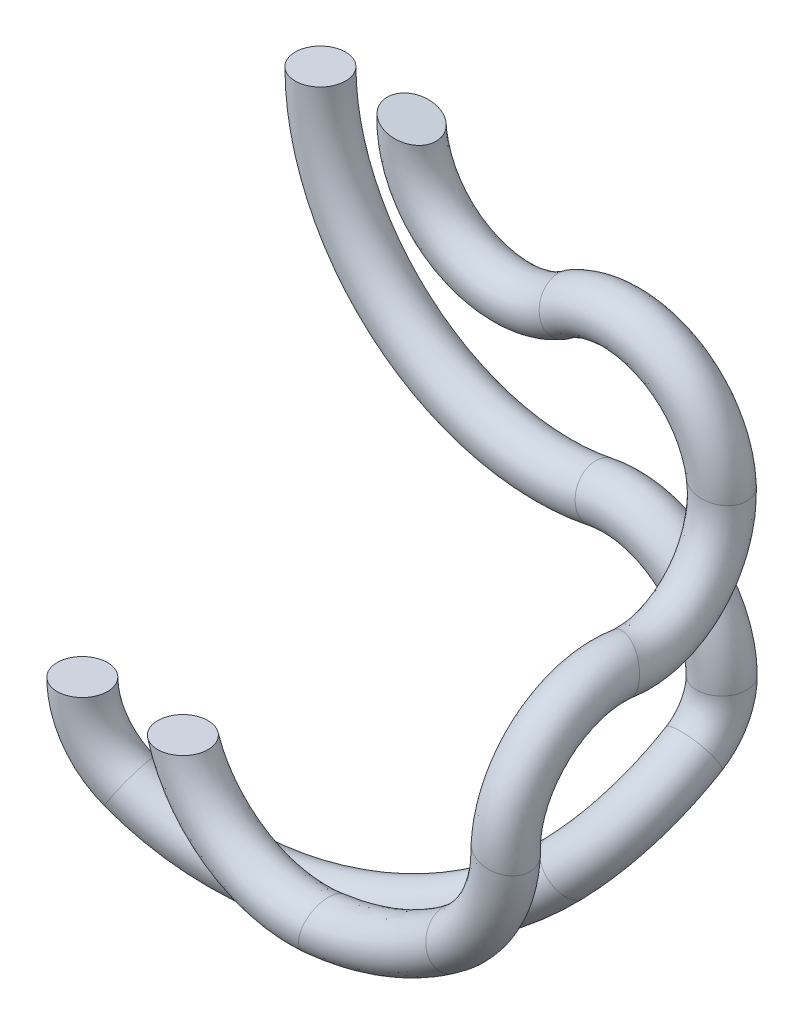
SolidWorks part; units mm, degrees
material "Magnesium Alloy"
ref_plane "Front Plane" through (0, 0, 0) normal (0, 0, 1) x (1, 0, 0)
ref_plane "Top Plane" through (0, 0, 0) normal (0, 1, 0) x (1, 0, 0)
ref_plane "Right Plane" through (0, 0, 0) normal (1, 0, 0) x (0, 0, -1)
sketch "Sketch2" plane through (0, 0, 0) normal (0, 1, 0) x (1, 0, 0)
  circle A0 centre (0, 0) radius 3
  dimension "D1" = 6
ref_plane "Plane1" through (37, 0, 0) normal (1, 0, 0) x (0, 0, -1)
ref_plane "Plane2" through (0, 0, -27.3) normal (0, 0, 1) x (1, 0, 0)
sketch "Sketch3" plane through (0, 0, 0) normal (0, 0, 1) x (1, 0, 0)
  line L0 (37, -15.125) -> (37, 15.125) construction
  arc A0 (0, 50) -> (18.4268, 40.0396) centre (11.9054, 50) ccw
  arc A1 (18.4268, 40.0396) -> (37, 30) centre (25, 30) cw
  dimension "D1" = 12
  dimension "D2" = 50
  dimension "D3" = 30
sketch "Sketch4" plane through (0, 0, 0) normal (1, 0, 0) x (0, 0, -1)
  line L0 (24.5, 30) -> (0, 30) construction
  line L1 (10.7134, 14.4646) -> (0, 0) construction
  arc A0 (10.7134, 14.4646) -> (16.4282, 18.6612) centre (20.3564, 7.3223) cw
  arc A1 (16.4282, 18.6612) -> (24.5, 30) centre (12.5, 30) ccw
  dimension "D2" = 12
  dimension "D4" = 12
  dimension "D1" = 24.5
  dimension "D3" = 18
sketch "Sketch6" plane through (0, 0, -27.3) normal (0, 0, 1) x (1, 0, 0)
  arc A0 (0, 50) -> (18.4268, 40.0396) centre (11.9054, 50) ccw construction
  arc A1 (37, 30) -> (18.4268, 40.0396) centre (25, 30) ccw construction
  arc A2 (0, 50) -> (18.4268, 40.0396) centre (11.9054, 50) ccw
  arc A3 (37, 30) -> (18.4268, 40.0396) centre (25, 30) ccw
sketch "Sketch7" plane through (37, 0, 0) normal (1, 0, 0) x (0, 0, -1)
  arc A0 (16.4282, 18.6612) -> (10.7134, 14.4646) centre (20.3564, 7.3223) ccw construction
  arc A1 (16.4282, 18.6612) -> (24.5, 30) centre (12.5, 30) ccw construction
  arc A2 (16.4282, 18.6612) -> (10.7134, 14.4646) centre (20.3564, 7.3223) ccw
  arc A3 (16.4282, 18.6612) -> (24.5, 30) centre (12.5, 30) ccw
sketch "Sketch8" plane through (0, 0, 0) normal (0, 0, 1) x (1, 0, 0)
  line L0 (3, 0) -> (-3, 0) construction
  arc A1 (0, 0) -> (16.848, -11) centre (15.0295, 4.6172) ccw
  arc A2 (16.848, -11) -> (32.1489, -4.9619) centre (13.1469, 20.7846) ccw
  arc A3 (32.1489, -4.9619) -> (37, 14.4646) centre (22.8124, 7.6885) ccw
  dimension "D1" = 31.9994
  dimension "D2" = 11
sketch3d "3DSketch2"
  line L0 (36.9546, 31.0431, -27.3) -> (38.5338, 7.49, 0) construction
  arc A1 (0, 0, 0) -> (16.848, -11, 0) centre (15.0295, 4.6172, 0) ccw construction
  arc A2 (16.848, -11, 0) -> (32.1489, -4.9619, 0) centre (13.1469, 20.7846, 0) ccw construction
  arc A3 (37, 30, -27.3) -> (18.4268, 40.0396, -27.3) centre (25, 30, -27.3) ccw construction
  arc A4 (0, 50, -27.3) -> (18.4268, 40.0396, -27.3) centre (11.9054, 50, -27.3) ccw construction
  arc A5 (32.1489, -4.9619, 0) -> (37, 14.4646, 0) centre (22.8124, 7.6885, 0) ccw construction
  arc A6 (38.4122, 19.5675, -13.9693) -> (38.5338, 7.49, 0) centre (38.2944, 7.493, -12.2015) ccw
  arc A7 (38.4122, 19.5675, -13.9693) -> (36.9546, 31.0431, -27.3) centre (37.351, 31.0777, -15.6292) ccw
  arc A8 (36.9546, 31.0431, -27.3) -> (18.4268, 40.0396, -27.3) centre (25, 30, -27.3) ccw
  arc A9 (0, 50, -27.3) -> (18.4268, 40.0396, -27.3) centre (11.9054, 50, -27.3) ccw
  arc A10 (0, 0, 0) -> (16.848, -11, 0) centre (15.0295, 4.6172, 0) ccw
  arc A11 (16.848, -11, 0) -> (32.1489, -4.9619, 0) centre (13.1469, 20.7846, 0) ccw
  arc A12 (32.1489, -4.9619, 0) -> (38.5338, 7.49, 0) centre (22.8124, 7.6885, 0) ccw
  point P3 (15.0295, 4.6172, 15.7227)
  point P13 (25, 30, -15.3)
  point P16 (11.9054, 50, -15.3946)
  point P17 (50.4949, 7.3389, -12.4409)
  point P18 (48.9776, 32.0921, -16.0272)
  point P19 (25, 30, -15.3)
  point P20 (11.9054, 50, -15.3946)
  point P23 (13.1469, 20.7846, 31.9994)
  point P24 (15.0295, 4.6172, 15.7227)
  point P26 (22.8124, 7.6885, 15.7227)
  point P27 (13.1469, 20.7846, 31.9994)
  point P28 (22.8124, 7.6885, 15.7227)
sweep "Sweep1" add profiles "Sketch2" path "3DSketch2"
sketch "Sketch9" plane through (0, 0, 0) normal (0, 0, 1) x (1, 0, 0)
  arc A0 (37, 0) -> (-12, 0) centre (12.5, 0) cw construction
  dimension "D1" = 12
sketch "Sketch10" plane through (37, 0, 0) normal (1, 0, 0) x (0, 0, -1)
  arc A0 (19.9191, 0.4646) -> (23.4888, 4.8271) centre (26.5822, -1.3458) cw
  arc A1 (23.4888, 4.8271) -> (27.3, 11) centre (20.3953, 11) ccw
  point P5 (0, 0)
  dimension "D1" = 14
  dimension "D2" = 11
sketch "Sketch11" plane through (0, 0, -27.3) normal (0, 0, 1) x (1, 0, 0)
  arc A0 (-10.89, 50) -> (22.5699, 22.7514) centre (16.9351, 50) ccw
  arc A1 (22.5699, 22.7514) -> (37, 11) centre (25, 11) cw
  dimension "D2" = 12
  dimension "D1" = 10.89
sketch3d "3DSketch3"
  line L0 (-12, 0, 0) -> (-12, 11.5276, 0) construction
  line L1 (-12, 0, 0) -> (31.5832, 0, 0) construction
  line L2 (31.5832, 0, 0) -> (31.5832, 0, -14) construction
  line L3 (31.5832, 0, -14) -> (31.5832, -4.9493, -14) construction
  line L4 (12, 0, 0) -> (12, 0, -6) construction
  line L5 (12, 0, -6) -> (12, -14, -6) construction
  arc A0 (-7.2107, -8.8412, -0.9153) -> (31.5832, -4.9493, -14) centre (8.3648, 18.4815, -11.2394) cw
  arc A2 (37, 4.8271, -23.4888) -> (37, 11, -27.3) centre (37, 11, -20.3953) ccw construction
  arc A3 (22.5699, 22.7514, -27.3) -> (37, 11, -27.3) centre (25, 11, -27.3) ccw construction
  arc A4 (-10.89, 50, -27.3) -> (22.5699, 22.7514, -27.3) centre (16.9351, 50, -27.3) ccw construction
  arc A6 (37, 5.1024, -23.9859) -> (37, 11, -27.3) centre (37, 11, -20.3953) ccw
  arc A7 (22.5699, 22.7514, -27.3) -> (37, 11, -27.3) centre (25, 11, -27.3) ccw
  arc A8 (-10.89, 50, -27.3) -> (22.5699, 22.7514, -27.3) centre (16.9351, 50, -27.3) ccw
  arc A9 (-12, 0, 0) -> (-7.2107, -8.8412, -0.9153) centre (-1.7323, 0, -1.9623) cw
  arc A10 (31.5832, -4.9493, -14) -> (37, 5.1024, -23.9859) centre (21.7451, -3.0586, -28.9545) cw
  arc A12 (37, 0, 0) -> (-12, 0, 0) centre (12.5, 0, 0) ccw construction
  point P10 (18.2112, 24.5853, 19.7688)
  point P12 (43.9047, 11, -20.3953)
  point P15 (25, 11, -39.3)
  point P18 (16.9351, 50, 0.5251)
  point P19 (43.9047, 11, -20.3953)
  point P20 (25, 11, -39.3)
  point P21 (16.9351, 50, 0.5251)
  point P24 (12.1906, 9.9714, -21.0216)
  point P28 (0.23, 0, 8.3054)
  point P33 (12.5, 0, -24.5)
  dimension "D1" = 18
  dimension "D3" = 14
  dimension "D2" = 24
  dimension "D4" = 14
  dimension "D5" = 6
sketch "Sketch12" plane through (0, 0, 0) normal (0, 1, 0) x (1, 0, 0)
  circle A0 centre (-12, 0) radius 3
  circle A2 centre (0, 0) radius 3 construction
sweep "Sweep2" add profiles "Sketch12" path "3DSketch3"
